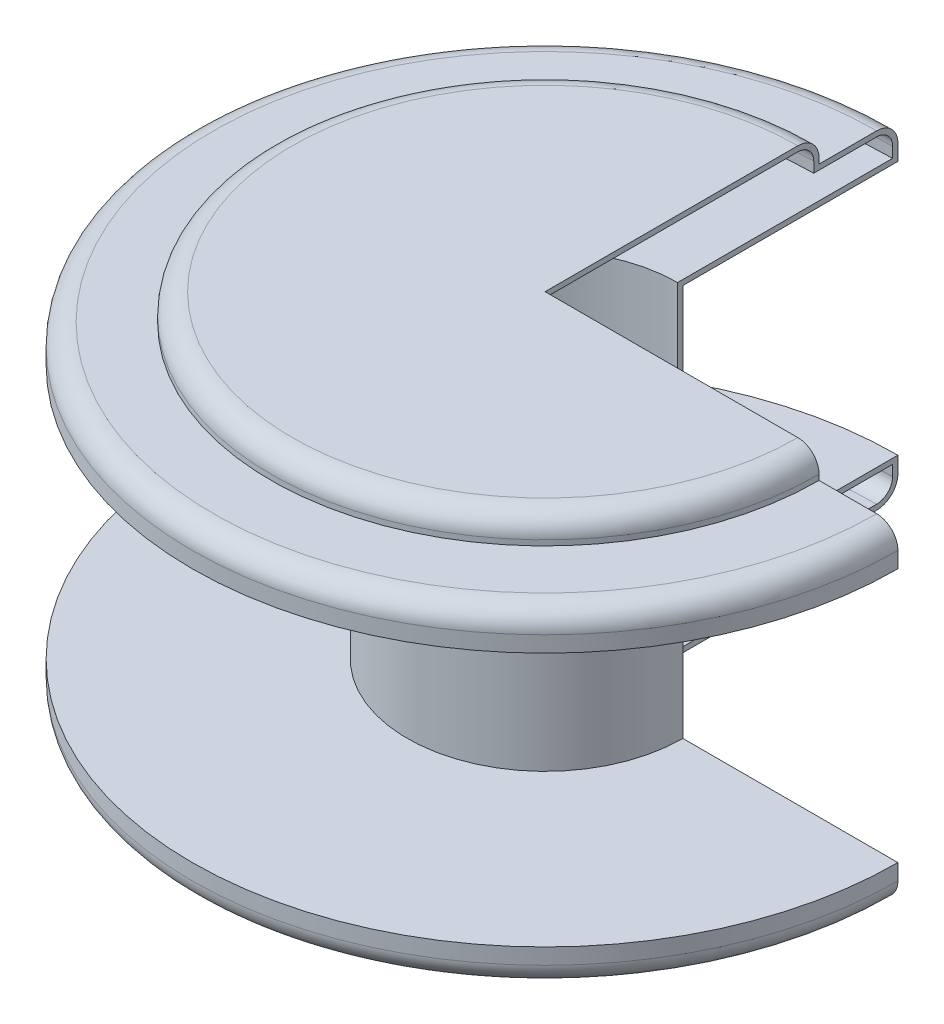
SolidWorks part; units mm, degrees
ref_plane "Front Plane" through (0, 0, 0) normal (0, 0, 1) x (1, 0, 0)
ref_plane "Top Plane" through (0, 0, 0) normal (0, 1, 0) x (1, 0, 0)
ref_plane "Right Plane" through (0, 0, 0) normal (1, 0, 0) x (0, 0, -1)
sketch "Sketch1" plane through (0, 0, 0) normal (0, 0, 1) x (1, 0, 0)
  line L0 (0, 25) -> (0, -25)
  line L1 (0, -25) -> (40.5663, -25)
  line L2 (40.5663, -25) -> (40.5663, -27)
  line L3 (37.5663, -30) -> (25.692, -30)
  line L4 (25.692, -30) -> (25.692, -32)
  line L5 (22.692, -35) -> (-25, -35)
  line L6 (-113.3151, 0) -> (113.3151, 0) construction
  line L7 (22.692, 35) -> (-25, 35)
  line L8 (25.692, 30) -> (25.692, 32)
  line L9 (37.5663, 30) -> (25.692, 30)
  line L10 (40.5663, 25) -> (40.5663, 27)
  line L11 (0, 25) -> (40.5663, 25)
  line L12 (-25, 35) -> (-25, -35) construction
  arc A0 (37.5663, -30) -> (40.5663, -27) centre (37.5663, -27) ccw
  arc A1 (22.692, -35) -> (25.692, -32) centre (22.692, -32) ccw
  arc A2 (22.692, 35) -> (25.692, 32) centre (22.692, 32) cw
  arc A3 (37.5663, 30) -> (40.5663, 27) centre (37.5663, 27) cw
  point P11 (0, 0)
  point P25 (0, 0)
  dimension "D1" = 3
  dimension "D2" = 3
  dimension "D3" = 50
  dimension "D4" = 60
  dimension "D5" = 70
  dimension "D6" = 50
  dimension "D7" = 101.3839
revolve "Revolve-Thin4" add sketch "Sketch1" angle 270 about L12 wall 1
